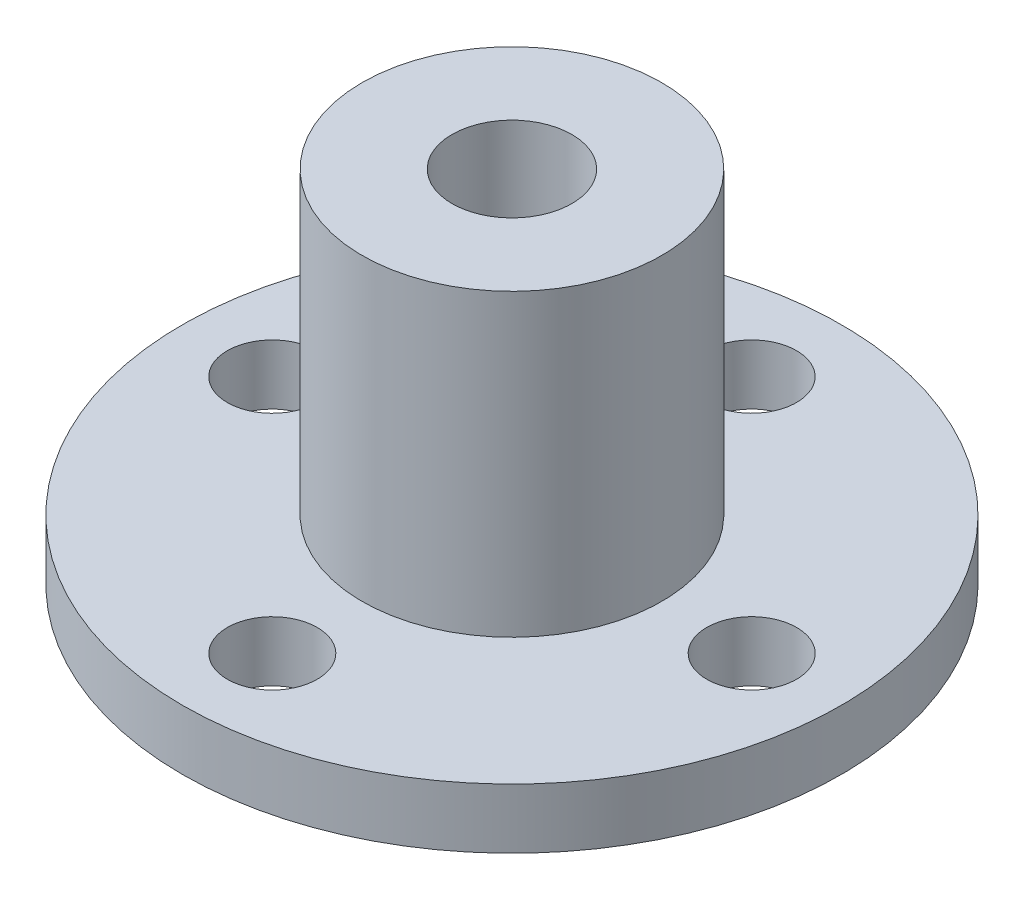
SolidWorks part; units mm, degrees
ref_plane "前视基准面" through (0, 0, 0) normal (0, 0, 1) x (1, 0, 0)
ref_plane "上视基准面" through (0, 0, 0) normal (0, 1, 0) x (1, 0, 0)
ref_plane "右视基准面" through (0, 0, 0) normal (1, 0, 0) x (0, 0, -1)
sketch "草图1" plane through (0, 0, 0) normal (0, 1, 0) x (0, 0, -1)
  circle A0 centre (0, 0) radius 11
  dimension "D1" = 22
extrude "凸台-拉伸1" add sketch "草图1" along normal blind 2
sketch "草图2" plane through (0, 2, 0) normal (0, 1, 0) x (0, 0, -1)
  circle A0 centre (0, 0) radius 5
  circle A1 centre (0, 0) radius 5
  dimension "D1" = 10
extrude "凸台-拉伸2" add sketch "草图2" along normal blind 10
sketch "草图3" plane through (0, 2, 0) normal (0, 1, 0) x (0, 0, -1)
  circle A0 centre (0, 0) radius 8 construction
  circle A1 centre (0, 8) radius 1.5
  circle A2 centre (0.001, 0.001) radius 8 construction
  circle A3 centre (8.001, 0.001) radius 1.5
  circle A4 centre (0.002, 0) radius 8 construction
  circle A5 centre (0.002, -8) radius 1.5
  circle A6 centre (0.001, -0.001) radius 8 construction
  circle A7 centre (-7.999, -0.001) radius 1.5
  point P20 (0.001, 0)
  dimension "D1" = 3
  dimension "D2" = 4
extrude "切除-拉伸1" cut sketch "草图3" against normal blind 10
sketch "草图5" plane through (0, 12, 0) normal (0, 1, 0) x (1, 0, 0)
  circle A0 centre (0, 0) radius 2
  dimension "D1" = 4
extrude "切除-拉伸2" cut sketch "草图5" against normal through all
